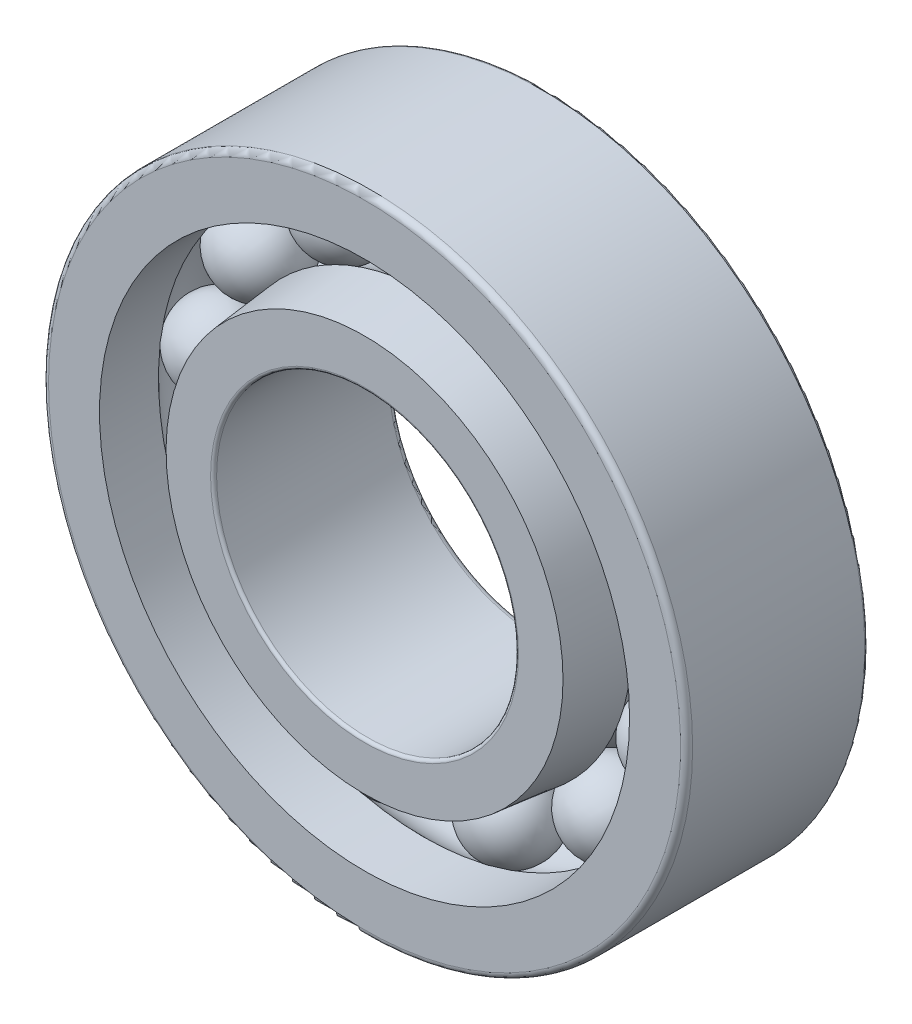
SolidWorks part; units mm, degrees
ref_plane "Front Plane" through (0, 0, 0) normal (0, 0, 1) x (1, 0, 0)
ref_plane "Top Plane" through (0, 0, 0) normal (0, 1, 0) x (1, 0, 0)
ref_plane "Right Plane" through (0, 0, 0) normal (1, 0, 0) x (0, 0, -1)
sketch "BaseSke" plane through (0, 0, 0) normal (1, 0, 0) x (0, 0, -1)
  line L0 (-47.2296, 0) -> (24.6132, 0) construction
  line L1 (-47.2296, 11.75) -> (24.6132, 11.75) construction
  line L2 (0, 129.5214) -> (0, -86.3012) construction
  line L3 (0, 13.875) -> (0, 9.625)
  line L4 (-4.5, 16) -> (4.5, 16) construction
  line L5 (-4.5, 7.5) -> (4.5, 7.5) construction
  arc A0 (0, 13.875) -> (0, 9.625) centre (0, 11.75) ccw
  dimension "Ball_diameter" = 4.25
  dimension "Bearing_Thickness" = 9
  dimension "Bearing_Outside_Diameter" = 32
  dimension "Bearing_Inside_Diameter" = 15
  dimension "D1" = 11.75
revolve "Ball" add sketch "BaseSke" angle 360 about L3
sketch "OuterRaceSke" plane through (0, 0, 0) normal (1, 0, 0) x (0, 0, -1)
  line L0 (0, 0) -> (0, 87.5396) construction
  line L1 (-4.5, 16) -> (4.5, 16)
  line L2 (-4.5, 16) -> (-4.5, 13.1667)
  line L3 (-4.5, 13.1667) -> (-1.5704, 13.1667)
  line L4 (4.5, 16) -> (4.5, 13.6396)
  line L5 (-50.3916, 0) -> (55.2197, 0) construction
  line L6 (-47.2296, 11.75) -> (24.6132, 11.75) construction
  line L8 (4.5, 13.6396) -> (1.4215, 13.3161)
  line L9 (0, 13.1667) -> (-11.5325, 56.2065) construction
  line L10 (0, 13.1667) -> (1.4215, 13.3161) construction
  arc A0 (1.4215, 13.3161) -> (-1.5704, 13.1667) centre (0, 11.75) ccw
  dimension "D4" = 4.23
  dimension "D2" = 26.3333
  dimension "Angle" = 15
  dimension "D3" = 6
revolve "OuterRace" add sketch "OuterRaceSke" angle 360 about L5
sketch "InnerRaceSke" plane through (0, 0, 0) normal (1, 0, 0) x (0, 0, -1)
  line L0 (-70.8626, 0) -> (113.5527, 0) construction
  line L1 (0, 58.441) -> (0, -70.8113) construction
  line L2 (-4.5, 7.5) -> (4.5, 7.5)
  line L3 (-4.5, 7.5) -> (-4.5, 10.3333)
  line L4 (-4.5, 10.3333) -> (-1.5704, 10.3333)
  line L5 (4.5, 7.5) -> (4.5, 10.3333)
  line L6 (0, 129.5214) -> (0, -86.3012) construction
  line L7 (1.5704, 10.3333) -> (4.5, 10.3333)
  arc A0 (-1.5704, 10.3333) -> (1.5704, 10.3333) centre (0, 11.75) ccw
  arc A1 (0, 13.875) -> (0, 9.625) centre (0, 11.75) ccw construction
  dimension "D2" = 4.23
  dimension "D1" = 20.6667
revolve "InnerRace" add sketch "InnerRaceSke" angle 360 about L0
fillet "Fillet1" radius 0.3 2 edges at (7.5, 0, -4.5) (16, 0, 4.5)
fillet "Fillet2" radius 0.15 2 edges at (16, 0, -4.5) (7.5, 0, 4.5)
sketch "CutInnerRaceSke" plane through (0, 0, 0) normal (1, 0, 0) x (0, 0, -1)
  line L0 (-1.5704, 10.3333) -> (-4.5, 10.3333)
  line L1 (-4.5, 10.3333) -> (-4.5, 9.8604)
  line L2 (-4.5, 9.8604) -> (-1.4215, 10.1839)
  line L3 (-1.4215, 10.1839) -> (0, 10.3333) construction
  line L4 (0, 58.441) -> (0, -70.8113) construction
  line L5 (-28.3066, 0) -> (35.2466, 0) construction
  arc A0 (-1.5704, 10.3333) -> (-1.4215, 10.1839) centre (0, 11.75) ccw
  arc A1 (-1.5704, 10.3333) -> (1.5704, 10.3333) centre (0, 11.75) ccw construction
  dimension "D1" = 6
revolve "CutInnerRace" cut sketch "CutInnerRaceSke" angle 360 about L5
pattern_circular "CirPatternBall" count 13 over 360 about axis through (0, 0, 0) along (0, 0, 1) of "Ball"
sketch "SimplifiedSke" plane through (0, 0, 0) normal (1, 0, 0) x (0, 0, -1)
  line L0 (37.5911, 0) -> (-37.5911, 0) construction
  circle A0 centre (0, 11.75) radius 2.125
  arc A1 (0, 13.875) -> (0, 9.625) centre (0, 11.75) ccw construction
revolve "Simplified" [suppressed] add sketch "SimplifiedSke" angle 360 about L0
equation "\"D1@BaseSke\" =  (\"Bearing_Outside_Diameter@BaseSke\"  +  \"Bearing_Inside_Diameter@BaseSke\"  )  / 4"
equation "\"Ball_diameter@BaseSke\" =  ( \"Bearing_Outside_Diameter@BaseSke\" - \"Bearing_Inside_Diameter@BaseSke\" ) / 4 "
equation "\"D2@OuterRaceSke\" = \"Bearing_Outside_Diameter@BaseSke\" -  ( \"Bearing_Outside_Diameter@BaseSke\" - \"Bearing_Inside_Diameter@BaseSke\" )  / 3"
equation "\"D4@OuterRaceSke\" = (  \"Bearing_Outside_Diameter@BaseSke\" - \"Bearing_Inside_Diameter@BaseSke\" ) / 4 -0.02"
equation "\"D3@OuterRaceSke\" = \"Angle@OuterRaceSke\"/2.5"
equation "\"D1@InnerRaceSke\" = \"Bearing_Inside_Diameter@BaseSke\" +  ( \"Bearing_Outside_Diameter@BaseSke\" - \"Bearing_Inside_Diameter@BaseSke\" )  / 3"
equation "\"D2@InnerRaceSke\" = \"D4@OuterRaceSke\""
equation "\"D1@CirPatternBall\" = int( \"D1@BaseSke\"* pi  * 2 / \"Ball_diameter@BaseSke\"/1.2 ) -1"
equation "\"D1@CutInnerRaceSke\" = \"D3@OuterRaceSke\""
